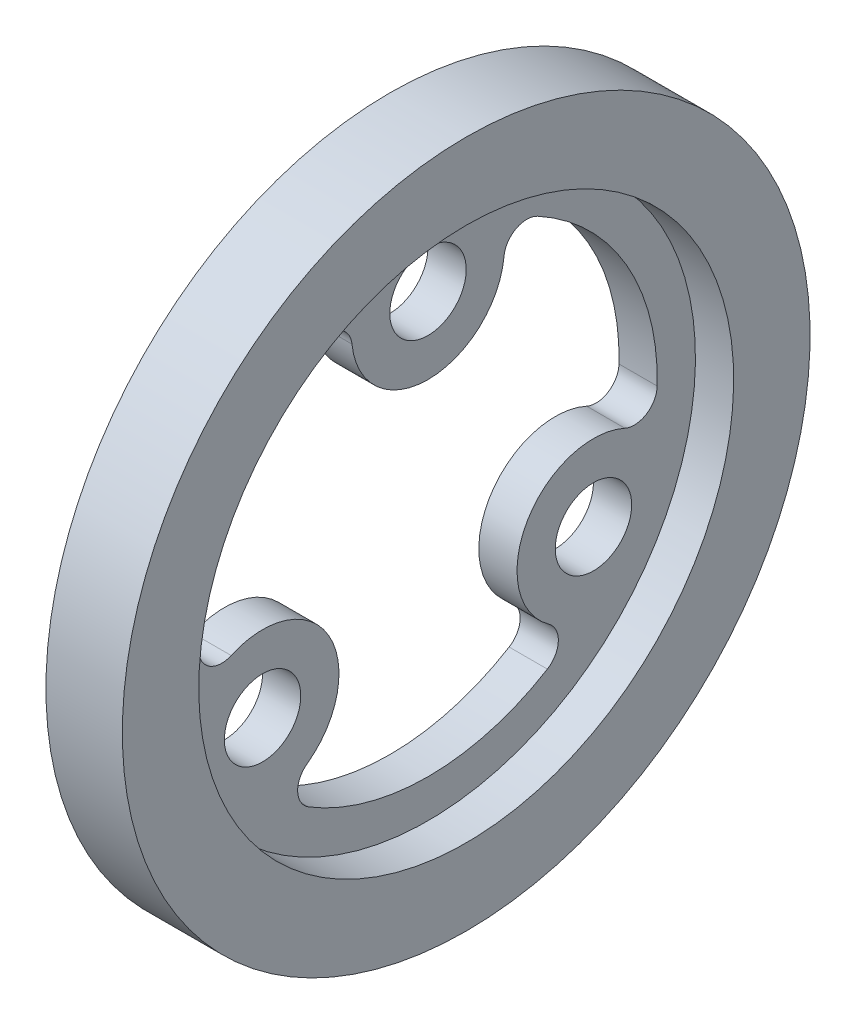
SolidWorks part; units mm, degrees
ref_plane "Alzado" through (0, 0, 0) normal (0, 0, 1) x (1, 0, 0)
ref_plane "Planta" through (0, 0, 0) normal (0, 1, 0) x (1, 0, 0)
ref_plane "Vista lateral" through (0, 0, 0) normal (1, 0, 0) x (0, 0, -1)
sketch "Croquis1" plane through (0, 0, 0) normal (0, 0, 1) x (1, 0, 0)
  line L0 (2.3015, 0) -> (-29.5031, 0) construction
  line L1 (0, 0) -> (0, 45)
  line L2 (0, 45) -> (10, 45)
  line L3 (10, 45) -> (10, 0)
  line L4 (0, 0) -> (10, 0)
  dimension "D1" = 45
  dimension "D2" = 10
revolve "Revolución1" add sketch "Croquis1" angle 360 about L4
sketch "Croquis2" plane through (10, 0, 0) normal (1, 0, 0) x (0, 0, -1)
  circle A0 centre (0, 0) radius 35
  dimension "D1" = 70
extrude "Cortar-Extruir1" cut sketch "Croquis2" against normal blind 5
sketch "Croquis4" plane through (5, 0, 0) normal (1, 0, 0) x (0, 0, -1)
  circle A0 centre (0, 0) radius 30
  circle A1 centre (0, 0) radius 25
  arc A2 (-9.9499, 24) -> (9.9499, 24) centre (0, 25) ccw
  circle A3 centre (0, 25) radius 5
  arc A4 (14.372, 26.3333) -> (9.9499, 24) centre (12.9348, 23.7) ccw
  arc A5 (-9.9499, 24) -> (-14.372, 26.3333) centre (-12.9348, 23.7) ccw
  circle A6 centre (21.6506, -12.5) radius 5
  arc A7 (25.7595, -3.3832) -> (15.8097, -20.6168) centre (21.6506, -12.5) ccw
  arc A8 (25.7595, -3.3832) -> (29.9914, -0.7201) centre (26.9922, -0.6481) ccw
  arc A9 (15.6193, -25.6132) -> (15.8097, -20.6168) centre (14.0574, -23.0519) ccw
  circle A10 centre (-21.6506, -12.5) radius 5
  arc A11 (-15.8097, -20.6168) -> (-25.7595, -3.3832) centre (-21.6506, -12.5) ccw
  arc A12 (-15.8097, -20.6168) -> (-15.6193, -25.6132) centre (-14.0574, -23.0519) ccw
  arc A13 (-29.9914, -0.7201) -> (-25.7595, -3.3832) centre (-26.9922, -0.6481) ccw
  point P30 (0, 0)
  point P31 (1.4689, 2.7843)
  dimension "D1" = 50
  dimension "D2" = 60
  dimension "D3" = 10
  dimension "D4" = 20
  dimension "D5" = 6
  dimension "D6" = 6
extrude "Cortar-Extruir3" cut sketch "Croquis4" against normal blind 5 contours A11 A1 A7 A2 | A1 A10 | A1 A10 | A1 A6 | A1 A6 | A1 A3 | A3 A1 | A11 A12 A0 A9 A7 A1 | A0 A13 A11 A1 A2 A5 | A7 A8 A0 A4 A2 A1
